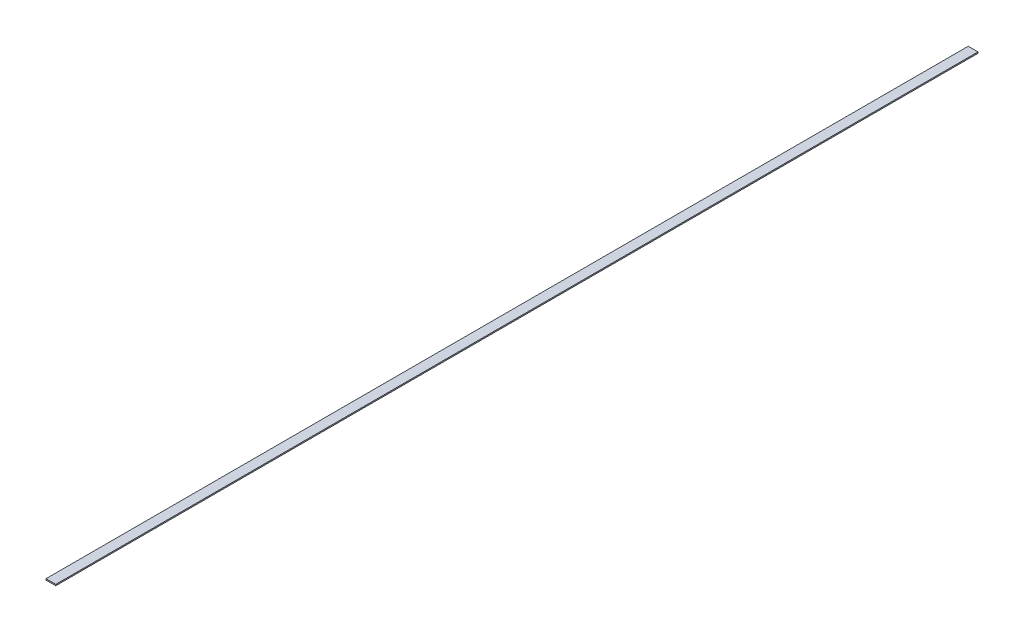
SolidWorks part; units mm, degrees
ref_plane "front" through (0, 0, 0) normal (0, 0, 1) x (1, 0, 0)
ref_plane "top" through (0, 0, 0) normal (0, 1, 0) x (1, 0, 0)
ref_plane "right" through (0, 0, 0) normal (1, 0, 0) x (0, 0, -1)
sketch "Sketch1" plane through (0, 0, 0) normal (0, 1, 0) x (1, 0, 0)
  line L1 (-7.9375, 0) -> (7.9375, 0)
  line L2 (-7.9375, 0) -> (-7.9375, 1498.6)
  line L3 (-7.9375, 1498.6) -> (7.9375, 1498.6)
  line L4 (7.9375, 0) -> (7.9375, 1498.6)
  dimension "D1" = 15.875
  dimension "D2" = 1498.6
extrude "Extrude1" add sketch "Sketch1" along normal blind 2.032
